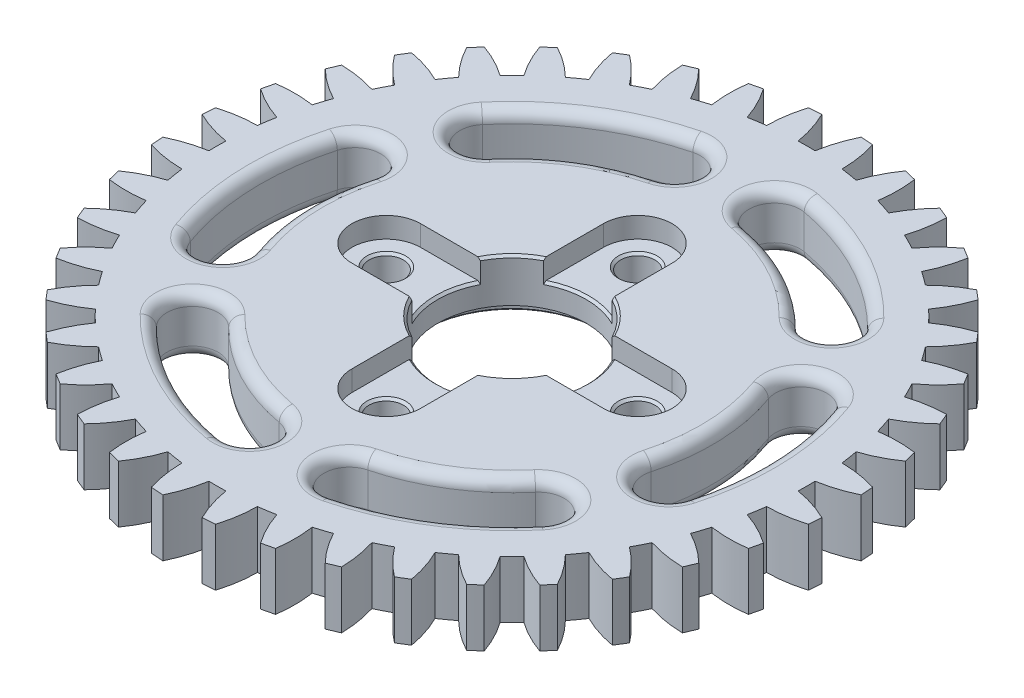
SolidWorks part; units mm, degrees
material "尼龙 101"
ref_plane "前视基准面" through (0, 0, 0) normal (0, 0, 1) x (1, 0, 0)
ref_plane "上视基准面" through (0, 0, 0) normal (0, 1, 0) x (1, 0, 0)
ref_plane "右视基准面" through (0, 0, 0) normal (1, 0, 0) x (0, 0, -1)
sketch "草图2" plane through (0, 0, 0) normal (0, 1, 0) x (1, 0, 0)
  line L0 (0, -1060.6686) -> (0, -25.7803) construction
  line L1 (0, 0) -> (39.3659, 0) construction
  line L2 (0, -12.5) -> (0, 15.5) construction
  line L3 (0, 25.7803) -> (0, 1032.0709) construction
  arc A127 (-0.7399, 25.7696) -> (-1.7209, 28.8237) centre (-11.5914, 23.9683) ccw
  arc A128 (-1.7209, 28.8237) -> (-2.8093, 28.738) centre (0, 0) ccw
  arc A129 (-2.8093, 28.738) -> (-3.3005, 25.5681) centre (7.6992, 25.4865) ccw
  arc A169 (0.7399, 25.7696) -> (-0.7399, 25.7696) centre (0, 0) ccw
  arc A170 (3.3005, 25.5681) -> (2.8093, 28.738) centre (-7.6992, 25.4865) ccw
  arc A171 (2.8093, 28.738) -> (1.7209, 28.8237) centre (0, 0) ccw
  arc A172 (1.7209, 28.8237) -> (0.7399, 25.7696) centre (11.5914, 23.9683) ccw
  arc A173 (7.2596, 24.737) -> (7.2703, 27.9447) centre (-3.6174, 26.3772) ccw
  arc A174 (7.2703, 27.9447) -> (6.2088, 28.1996) centre (0, 0) ccw
  arc A175 (6.2088, 28.1996) -> (4.762, 25.3366) centre (15.1981, 21.8599) ccw
  arc A176 (11.0399, 23.2968) -> (11.5523, 26.4634) centre (0.5534, 26.6183) ccw
  arc A177 (11.5523, 26.4634) -> (10.5437, 26.8811) centre (0, 0) ccw
  arc A178 (10.5437, 26.8811) -> (8.6669, 24.2797) centre (18.4307, 19.2133) ccw
  arc A179 (14.5485, 21.2829) -> (15.5499, 24.3304) centre (4.7106, 26.204) ccw
  arc A180 (15.5499, 24.3304) -> (14.619, 24.9008) centre (0, 0) ccw
  arc A181 (14.619, 24.9008) -> (12.3584, 22.625) centre (21.2094, 16.0936) ccw
  arc A182 (17.6987, 18.745) -> (19.1645, 21.5983) centre (8.7518, 25.1445) ccw
  arc A183 (19.1645, 21.5983) -> (18.3344, 22.3073) centre (0, 0) ccw
  arc A184 (18.3344, 22.3073) -> (15.7456, 20.4132) centre (23.4658, 12.5775) ccw
  arc A185 (20.4132, 15.7456) -> (22.3073, 18.3344) centre (12.5775, 23.4658) ccw
  arc A186 (22.3073, 18.3344) -> (21.5983, 19.1645) centre (0, 0) ccw
  arc A187 (21.5983, 19.1645) -> (18.745, 17.6987) centre (25.1445, 8.7518) ccw
  arc A188 (22.625, 12.3584) -> (24.9008, 14.619) centre (16.0936, 21.2094) ccw
  arc A189 (24.9008, 14.619) -> (24.3304, 15.5499) centre (0, 0) ccw
  arc A190 (24.3304, 15.5499) -> (21.2829, 14.5485) centre (26.204, 4.7106) ccw
  arc A191 (24.2797, 8.6669) -> (26.8811, 10.5437) centre (19.2133, 18.4307) ccw
  arc A192 (26.8811, 10.5437) -> (26.4634, 11.5523) centre (0, 0) ccw
  arc A193 (26.4634, 11.5523) -> (23.2968, 11.0399) centre (26.6183, 0.5534) ccw
  arc A194 (25.3366, 4.762) -> (28.1996, 6.2088) centre (21.8599, 15.1981) ccw
  arc A195 (28.1996, 6.2088) -> (27.9447, 7.2703) centre (0, 0) ccw
  arc A196 (27.9447, 7.2703) -> (24.737, 7.2596) centre (26.3772, -3.6174) ccw
  arc A197 (25.7696, 0.7399) -> (28.8237, 1.7209) centre (23.9683, 11.5914) ccw
  arc A198 (28.8237, 1.7209) -> (28.738, 2.8093) centre (0, 0) ccw
  arc A199 (28.738, 2.8093) -> (25.5681, 3.3005) centre (25.4865, -7.6992) ccw
  arc A200 (25.5681, -3.3005) -> (28.738, -2.8093) centre (25.4865, 7.6992) ccw
  arc A201 (28.738, -2.8093) -> (28.8237, -1.7209) centre (0, 0) ccw
  arc A202 (28.8237, -1.7209) -> (25.7696, -0.7399) centre (23.9683, -11.5914) ccw
  arc A203 (24.737, -7.2596) -> (27.9447, -7.2703) centre (26.3772, 3.6174) ccw
  arc A204 (27.9447, -7.2703) -> (28.1996, -6.2088) centre (0, 0) ccw
  arc A205 (28.1996, -6.2088) -> (25.3366, -4.762) centre (21.8599, -15.1981) ccw
  arc A206 (23.2968, -11.0399) -> (26.4634, -11.5523) centre (26.6183, -0.5534) ccw
  arc A207 (26.4634, -11.5523) -> (26.8811, -10.5437) centre (0, 0) ccw
  arc A208 (26.8811, -10.5437) -> (24.2797, -8.6669) centre (19.2133, -18.4307) ccw
  arc A209 (21.2829, -14.5485) -> (24.3304, -15.5499) centre (26.204, -4.7106) ccw
  arc A210 (24.3304, -15.5499) -> (24.9008, -14.619) centre (0, 0) ccw
  arc A211 (24.9008, -14.619) -> (22.625, -12.3584) centre (16.0936, -21.2094) ccw
  arc A212 (18.745, -17.6987) -> (21.5983, -19.1645) centre (25.1445, -8.7518) ccw
  arc A213 (21.5983, -19.1645) -> (22.3073, -18.3344) centre (0, 0) ccw
  arc A214 (22.3073, -18.3344) -> (20.4132, -15.7456) centre (12.5775, -23.4658) ccw
  arc A215 (15.7456, -20.4132) -> (18.3344, -22.3073) centre (23.4658, -12.5775) ccw
  arc A216 (18.3344, -22.3073) -> (19.1645, -21.5983) centre (0, 0) ccw
  arc A217 (19.1645, -21.5983) -> (17.6987, -18.745) centre (8.7518, -25.1445) ccw
  arc A218 (12.3584, -22.625) -> (14.619, -24.9008) centre (21.2094, -16.0936) ccw
  arc A219 (14.619, -24.9008) -> (15.5499, -24.3304) centre (0, 0) ccw
  arc A220 (15.5499, -24.3304) -> (14.5485, -21.2829) centre (4.7106, -26.204) ccw
  arc A221 (8.6669, -24.2797) -> (10.5437, -26.8811) centre (18.4307, -19.2133) ccw
  arc A222 (10.5437, -26.8811) -> (11.5523, -26.4634) centre (0, 0) ccw
  arc A223 (11.5523, -26.4634) -> (11.0399, -23.2968) centre (0.5534, -26.6183) ccw
  arc A224 (4.762, -25.3366) -> (6.2088, -28.1996) centre (15.1981, -21.8599) ccw
  arc A225 (6.2088, -28.1996) -> (7.2703, -27.9447) centre (0, 0) ccw
  arc A226 (7.2703, -27.9447) -> (7.2596, -24.737) centre (-3.6174, -26.3772) ccw
  arc A227 (0.7399, -25.7696) -> (1.7209, -28.8237) centre (11.5914, -23.9683) ccw
  arc A228 (1.7209, -28.8237) -> (2.8093, -28.738) centre (0, 0) ccw
  arc A229 (2.8093, -28.738) -> (3.3005, -25.5681) centre (-7.6992, -25.4865) ccw
  arc A230 (-3.3005, -25.5681) -> (-2.8093, -28.738) centre (7.6992, -25.4865) ccw
  arc A231 (-2.8093, -28.738) -> (-1.7209, -28.8237) centre (0, 0) ccw
  arc A232 (-1.7209, -28.8237) -> (-0.7399, -25.7696) centre (-11.5914, -23.9683) ccw
  arc A233 (-7.2596, -24.737) -> (-7.2703, -27.9447) centre (3.6174, -26.3772) ccw
  arc A234 (-7.2703, -27.9447) -> (-6.2088, -28.1996) centre (0, 0) ccw
  arc A235 (-6.2088, -28.1996) -> (-4.762, -25.3366) centre (-15.1981, -21.8599) ccw
  arc A236 (-11.0399, -23.2968) -> (-11.5523, -26.4634) centre (-0.5534, -26.6183) ccw
  arc A237 (-11.5523, -26.4634) -> (-10.5437, -26.8811) centre (0, 0) ccw
  arc A238 (-10.5437, -26.8811) -> (-8.6669, -24.2797) centre (-18.4307, -19.2133) ccw
  arc A239 (-14.5485, -21.2829) -> (-15.5499, -24.3304) centre (-4.7106, -26.204) ccw
  arc A240 (-15.5499, -24.3304) -> (-14.619, -24.9008) centre (0, 0) ccw
  arc A241 (-14.619, -24.9008) -> (-12.3584, -22.625) centre (-21.2094, -16.0936) ccw
  arc A242 (-17.6987, -18.745) -> (-19.1645, -21.5983) centre (-8.7518, -25.1445) ccw
  arc A243 (-19.1645, -21.5983) -> (-18.3344, -22.3073) centre (0, 0) ccw
  arc A244 (-18.3344, -22.3073) -> (-15.7456, -20.4132) centre (-23.4658, -12.5775) ccw
  arc A245 (-20.4132, -15.7456) -> (-22.3073, -18.3344) centre (-12.5775, -23.4658) ccw
  arc A246 (-22.3073, -18.3344) -> (-21.5983, -19.1645) centre (0, 0) ccw
  arc A247 (-21.5983, -19.1645) -> (-18.745, -17.6987) centre (-25.1445, -8.7518) ccw
  arc A248 (-22.625, -12.3584) -> (-24.9008, -14.619) centre (-16.0936, -21.2094) ccw
  arc A249 (-24.9008, -14.619) -> (-24.3304, -15.5499) centre (0, 0) ccw
  arc A250 (-24.3304, -15.5499) -> (-21.2829, -14.5485) centre (-26.204, -4.7106) ccw
  arc A251 (-24.2797, -8.6669) -> (-26.8811, -10.5437) centre (-19.2133, -18.4307) ccw
  arc A252 (-26.8811, -10.5437) -> (-26.4634, -11.5523) centre (0, 0) ccw
  arc A253 (-26.4634, -11.5523) -> (-23.2968, -11.0399) centre (-26.6183, -0.5534) ccw
  arc A254 (-25.3366, -4.762) -> (-28.1996, -6.2088) centre (-21.8599, -15.1981) ccw
  arc A255 (-28.1996, -6.2088) -> (-27.9447, -7.2703) centre (0, 0) ccw
  arc A256 (-27.9447, -7.2703) -> (-24.737, -7.2596) centre (-26.3772, 3.6174) ccw
  arc A257 (-25.7696, -0.7399) -> (-28.8237, -1.7209) centre (-23.9683, -11.5914) ccw
  arc A258 (-28.8237, -1.7209) -> (-28.738, -2.8093) centre (0, 0) ccw
  arc A259 (-28.738, -2.8093) -> (-25.5681, -3.3005) centre (-25.4865, 7.6992) ccw
  arc A260 (-25.5681, 3.3005) -> (-28.738, 2.8093) centre (-25.4865, -7.6992) ccw
  arc A261 (-28.738, 2.8093) -> (-28.8237, 1.7209) centre (0, 0) ccw
  arc A262 (-28.8237, 1.7209) -> (-25.7696, 0.7399) centre (-23.9683, 11.5914) ccw
  arc A263 (-24.737, 7.2596) -> (-27.9447, 7.2703) centre (-26.3772, -3.6174) ccw
  arc A264 (-27.9447, 7.2703) -> (-28.1996, 6.2088) centre (0, 0) ccw
  arc A265 (-28.1996, 6.2088) -> (-25.3366, 4.762) centre (-21.8599, 15.1981) ccw
  arc A266 (-23.2968, 11.0399) -> (-26.4634, 11.5523) centre (-26.6183, 0.5534) ccw
  arc A267 (-26.4634, 11.5523) -> (-26.8811, 10.5437) centre (0, 0) ccw
  arc A268 (-26.8811, 10.5437) -> (-24.2797, 8.6669) centre (-19.2133, 18.4307) ccw
  arc A269 (-21.2829, 14.5485) -> (-24.3304, 15.5499) centre (-26.204, 4.7106) ccw
  arc A270 (-24.3304, 15.5499) -> (-24.9008, 14.619) centre (0, 0) ccw
  arc A271 (-24.9008, 14.619) -> (-22.625, 12.3584) centre (-16.0936, 21.2094) ccw
  arc A272 (-18.745, 17.6987) -> (-21.5983, 19.1645) centre (-25.1445, 8.7518) ccw
  arc A273 (-21.5983, 19.1645) -> (-22.3073, 18.3344) centre (0, 0) ccw
  arc A274 (-22.3073, 18.3344) -> (-20.4132, 15.7456) centre (-12.5775, 23.4658) ccw
  arc A275 (-15.7456, 20.4132) -> (-18.3344, 22.3073) centre (-23.4658, 12.5775) ccw
  arc A276 (-18.3344, 22.3073) -> (-19.1645, 21.5983) centre (0, 0) ccw
  arc A277 (-19.1645, 21.5983) -> (-17.6987, 18.745) centre (-8.7518, 25.1445) ccw
  arc A278 (-12.3584, 22.625) -> (-14.619, 24.9008) centre (-21.2094, 16.0936) ccw
  arc A279 (-14.619, 24.9008) -> (-15.5499, 24.3304) centre (0, 0) ccw
  arc A280 (-15.5499, 24.3304) -> (-14.5485, 21.2829) centre (-4.7106, 26.204) ccw
  arc A281 (-8.6669, 24.2797) -> (-10.5437, 26.8811) centre (-18.4307, 19.2133) ccw
  arc A282 (-10.5437, 26.8811) -> (-11.5523, 26.4634) centre (0, 0) ccw
  arc A283 (-11.5523, 26.4634) -> (-11.0399, 23.2968) centre (-0.5534, 26.6183) ccw
  arc A284 (-4.762, 25.3366) -> (-6.2088, 28.1996) centre (-15.1981, 21.8599) ccw
  arc A285 (-6.2088, 28.1996) -> (-7.2703, 27.9447) centre (0, 0) ccw
  arc A286 (-7.2703, 27.9447) -> (-7.2596, 24.737) centre (3.6174, 26.3772) ccw
  circle A288 centre (0, -11) radius 1.5
  arc A289 (4.9213, -19.1408) -> (15.0876, -12.7653) centre (0, 0) ccw construction
  arc A290 (5.4782, -21.307) -> (16.7951, -14.21) centre (0, 0) ccw
  arc A291 (4.3643, -16.9745) -> (13.38, -11.3206) centre (0, 0) ccw
  arc A292 (4.3643, -16.9745) -> (5.4782, -21.307) centre (4.9213, -19.1408) ccw
  arc A293 (16.7951, -14.21) -> (13.38, -11.3206) centre (15.0876, -12.7653) ccw
  arc A294 (-12.5182, -12.2669) -> (-3.1139, -17.2478) centre (0, 0) ccw
  arc A295 (-12.5182, -12.2669) -> (-15.7133, -15.3978) centre (-14.1158, -13.8323) ccw
  arc A296 (-3.9087, -21.65) -> (-3.1139, -17.2478) centre (-3.5113, -19.4489) ccw
  arc A297 (-15.7133, -15.3978) -> (-3.9087, -21.65) centre (0, 0) ccw
  arc A298 (-14.1158, -13.8323) -> (-3.5113, -19.4489) centre (0, 0) ccw construction
  arc A299 (-16.8825, 4.7077) -> (-16.494, -5.9271) centre (0, 0) ccw
  arc A300 (-16.8825, 4.7077) -> (-21.1915, 5.9092) centre (-19.037, 5.3084) ccw
  arc A301 (-20.7038, -7.44) -> (-16.494, -5.9271) centre (-18.5989, -6.6836) ccw
  arc A302 (-21.1915, 5.9092) -> (-20.7038, -7.44) centre (0, 0) ccw
  arc A303 (-19.037, 5.3084) -> (-18.5989, -6.6836) centre (0, 0) ccw construction
  arc A304 (-4.3643, 16.9745) -> (-13.38, 11.3206) centre (0, 0) ccw
  arc A305 (-4.3643, 16.9745) -> (-5.4782, 21.307) centre (-4.9213, 19.1408) ccw
  arc A306 (-16.7951, 14.21) -> (-13.38, 11.3206) centre (-15.0876, 12.7653) ccw
  arc A307 (-5.4782, 21.307) -> (-16.7951, 14.21) centre (0, 0) ccw
  arc A308 (-4.9213, 19.1408) -> (-15.0876, 12.7653) centre (0, 0) ccw construction
  arc A309 (12.5182, 12.2669) -> (3.1139, 17.2478) centre (0, 0) ccw
  arc A310 (12.5182, 12.2669) -> (15.7133, 15.3978) centre (14.1158, 13.8323) ccw
  arc A311 (3.9087, 21.65) -> (3.1139, 17.2478) centre (3.5113, 19.4489) ccw
  arc A312 (15.7133, 15.3978) -> (3.9087, 21.65) centre (0, 0) ccw
  arc A313 (14.1158, 13.8323) -> (3.5113, 19.4489) centre (0, 0) ccw construction
  arc A314 (16.8825, -4.7077) -> (16.494, 5.9271) centre (0, 0) ccw
  arc A315 (16.8825, -4.7077) -> (21.1915, -5.9092) centre (19.037, -5.3084) ccw
  arc A316 (20.7038, 7.44) -> (16.494, 5.9271) centre (18.5989, 6.6836) ccw
  arc A317 (21.1915, -5.9092) -> (20.7038, 7.44) centre (0, 0) ccw
  arc A318 (19.037, -5.3084) -> (18.5989, 6.6836) centre (0, 0) ccw construction
  arc A322 (4.762, 25.3366) -> (3.3005, 25.5681) centre (0, 0) ccw
  arc A323 (8.6669, 24.2797) -> (7.2596, 24.737) centre (0, 0) ccw
  arc A324 (12.3584, 22.625) -> (11.0399, 23.2968) centre (0, 0) ccw
  arc A325 (15.7456, 20.4132) -> (14.5485, 21.2829) centre (0, 0) ccw
  arc A326 (18.745, 17.6987) -> (17.6987, 18.745) centre (0, 0) ccw
  arc A327 (21.2829, 14.5485) -> (20.4132, 15.7456) centre (0, 0) ccw
  arc A328 (23.2968, 11.0399) -> (22.625, 12.3584) centre (0, 0) ccw
  arc A329 (24.737, 7.2596) -> (24.2797, 8.6669) centre (0, 0) ccw
  arc A330 (25.5681, 3.3005) -> (25.3366, 4.762) centre (0, 0) ccw
  arc A331 (25.7696, -0.7399) -> (25.7696, 0.7399) centre (0, 0) ccw
  arc A332 (25.3366, -4.762) -> (25.5681, -3.3005) centre (0, 0) ccw
  arc A333 (24.2797, -8.6669) -> (24.737, -7.2596) centre (0, 0) ccw
  arc A334 (22.625, -12.3584) -> (23.2968, -11.0399) centre (0, 0) ccw
  arc A335 (20.4132, -15.7456) -> (21.2829, -14.5485) centre (0, 0) ccw
  arc A336 (17.6987, -18.745) -> (18.745, -17.6987) centre (0, 0) ccw
  arc A337 (14.5485, -21.2829) -> (15.7456, -20.4132) centre (0, 0) ccw
  arc A338 (11.0399, -23.2968) -> (12.3584, -22.625) centre (0, 0) ccw
  arc A339 (7.2596, -24.737) -> (8.6669, -24.2797) centre (0, 0) ccw
  arc A340 (3.3005, -25.5681) -> (4.762, -25.3366) centre (0, 0) ccw
  arc A341 (-4.762, -25.3366) -> (-3.3005, -25.5681) centre (0, 0) ccw
  arc A342 (-8.6669, -24.2797) -> (-7.2596, -24.737) centre (0, 0) ccw
  arc A343 (-12.3584, -22.625) -> (-11.0399, -23.2968) centre (0, 0) ccw
  arc A344 (-15.7456, -20.4132) -> (-14.5485, -21.2829) centre (0, 0) ccw
  arc A345 (-18.745, -17.6987) -> (-17.6987, -18.745) centre (0, 0) ccw
  arc A346 (-21.2829, -14.5485) -> (-20.4132, -15.7456) centre (0, 0) ccw
  arc A347 (-23.2968, -11.0399) -> (-22.625, -12.3584) centre (0, 0) ccw
  arc A348 (-24.737, -7.2596) -> (-24.2797, -8.6669) centre (0, 0) ccw
  arc A349 (-25.5681, -3.3005) -> (-25.3366, -4.762) centre (0, 0) ccw
  arc A350 (-25.3366, 4.762) -> (-25.5681, 3.3005) centre (0, 0) ccw
  arc A351 (-24.2797, 8.6669) -> (-24.737, 7.2596) centre (0, 0) ccw
  arc A352 (-22.625, 12.3584) -> (-23.2968, 11.0399) centre (0, 0) ccw
  arc A353 (-20.4132, 15.7456) -> (-21.2829, 14.5485) centre (0, 0) ccw
  arc A354 (-17.6987, 18.745) -> (-18.745, 17.6987) centre (0, 0) ccw
  arc A355 (-14.5485, 21.2829) -> (-15.7456, 20.4132) centre (0, 0) ccw
  arc A356 (-11.0399, 23.2968) -> (-12.3584, 22.625) centre (0, 0) ccw
  arc A357 (-7.2596, 24.737) -> (-8.6669, 24.2797) centre (0, 0) ccw
  arc A358 (-3.3005, 25.5681) -> (-4.762, 25.3366) centre (0, 0) ccw
  circle A360 centre (0, 0) radius 6.5
  circle A361 centre (-11, 0) radius 1.5
  circle A362 centre (0, 11) radius 1.5
  circle A363 centre (11, 0) radius 1.5
  arc A364 (-25.7696, 0.7399) -> (-25.7696, -0.7399) centre (0, 0) ccw
  arc A365 (-0.7399, -25.7696) -> (0.7399, -25.7696) centre (0, 0) ccw
  point P241 (0, 0)
  point P244 (10.5, -16.7433)
  point P254 (-9.2501, -17.4649)
  point P268 (-19.7501, -0.7216)
  point P275 (-10.5, 16.7433)
  point P282 (9.2501, 17.4649)
  point P289 (19.7501, 0.7216)
  point P294 (0, 0)
  point P302 (0, 1.5)
  point P308 (0, 0)
  dimension "D1" = 51.5605
  dimension "D4" = 26.6241
  dimension "D5" = 28.875
  dimension "D6" = 11
  dimension "D7" = 11
  dimension "D9" = 3
  dimension "D11" = 2.2367
  dimension "D12" = 22
  dimension "D17" = 13
  dimension "D2" = 25.7696
  dimension "D3" = 26.6241
  dimension "D8" = 25.5681
  dimension "D10" = 11
  dimension "D13" = 10.5
  dimension "D14" = 12
extrude "凸台-拉伸2" add sketch "草图2" along normal blind 5 contours A129 A358 A284 A285 A286 A357 A281 A282 A283 A356 A278 A279 A280 A355 A275 A276 A277 A354 A272 A273 A274 A353 A269 A270 A271 A352 A266 A267 A268 A351 A263 A264 A265 A350 A257 A258 A259 A349 A254 A255 A256 A348 A251 A252 A253 A347 A248 A249 A250
sketch "草图3" plane through (0, 5, 0) normal (0, 1, 0) x (1, 0, 0)
  line L0 (3, -11) -> (3, -5.2538)
  line L1 (-3, -11) -> (-3, -5.2538)
  line L2 (-11, -3) -> (-5.2538, -3)
  line L3 (-11, 3) -> (-5.2538, 3)
  line L4 (-3, 11) -> (-3, 5.2538)
  line L5 (3, 11) -> (3, 5.2538)
  line L6 (11, 3) -> (5.2538, 3)
  line L7 (11, -3) -> (5.2538, -3)
  circle A0 centre (0, 0) radius 6.05
  arc A1 (-3, -11) -> (3, -11) centre (0, -11) ccw
  arc A2 (-11, 3) -> (-11, -3) centre (-11, 0) ccw
  arc A3 (3, 11) -> (-3, 11) centre (0, 11) ccw
  arc A4 (11, -3) -> (11, 3) centre (11, 0) ccw
  point P27 (0, 0)
  dimension "D1" = 11
  dimension "D2" = 6
  dimension "D3" = 12.1
extrude "切除-拉伸1" cut sketch "草图3" against normal blind 1.8 contours L5 A3 L4 A0 | L7 A4 L6 A0 | L3 A2 L2 A0 | L1 A1 L0 A0
sketch "草图4" plane through (0, 0, 0) normal (0, -1, 0) x (1, 0, 0)
  circle A0 centre (0, 0) radius 7.6
  dimension "D1" = 15.2
extrude "切除-拉伸2" cut sketch "草图4" against normal blind 1.2 contours A0
chamfer "倒角1" distance 0.2 angle 45 17 edges at (0, 3.2, 12.5) (0, 0, 12.5) (-11, 3.2, 1.5) (-11, 0, 1.5) (11, 3.2, 1.5) (11, 0, 1.5) (0, 3.2, -9.5) (0, 0, -9.5) (-6.5, 3.2, 0) (-4.5962, 5, 4.5962) (4.5962, 5, 4.5962) (0, 3.2, 6.5) (6.5, 3.2, 0) (0, 3.2, -6.5) (4.5962, 5, -4.5962) (-4.5962, 5, -4.5962) (0, 0, -7.6)
fillet "圆角2" radius 1 48 edges at (-18.4363, 5, -7.4629) (-18.4363, 0, -7.4629) (-17.5149, 5, 0.6399) (-17.5149, 0, 0.6399) (-8.2033, 5, 15.4883) (-8.2033, 0, 15.4883) (-10.297, 5, 19.4415) (-10.297, 0, 19.4415) (-1.3102, 5, 19.8463) (-1.3102, 0, 19.8463) (-9.3117, 5, -14.8484) (-9.3117, 0, -14.8484) (-17.8425, 5, 8.7885) (-17.8425, 0, 8.7885) (-2.755, 5, -19.6977) (-2.755, 0, -19.6977) (-16.5323, 5, -11.0578) (-16.5323, 0, -11.0578) (-11.6883, 5, -18.6382) (-11.6883, 0, -18.6382) (-21.9853, 5, 0.8033) (-21.9853, 0, 0.8033) (-15.6812, 5, 12.2348) (-15.6812, 0, 12.2348) (2.755, 5, 19.6977) (2.755, 0, 19.6977) (9.3117, 5, 14.8484) (9.3117, 0, 14.8484) (16.5323, 5, 11.0578) (16.5323, 0, 11.0578) (11.6883, 5, 18.6382) (11.6883, 0, 18.6382) (18.4363, 5, 7.4629) (18.4363, 0, 7.4629) (21.9853, 5, -0.8033) (21.9853, 0, -0.8033) (17.8425, 5, -8.7885) (17.8425, 0, -8.7885) (17.5149, 5, -0.6399) (17.5149, 0, -0.6399) (8.2033, 5, -15.4883) (8.2033, 0, -15.4883) (1.3102, 5, -19.8463) (1.3102, 0, -19.8463) (15.6812, 5, -12.2348) (15.6812, 0, -12.2348) (10.297, 5, -19.4415) (10.297, 0, -19.4415)
